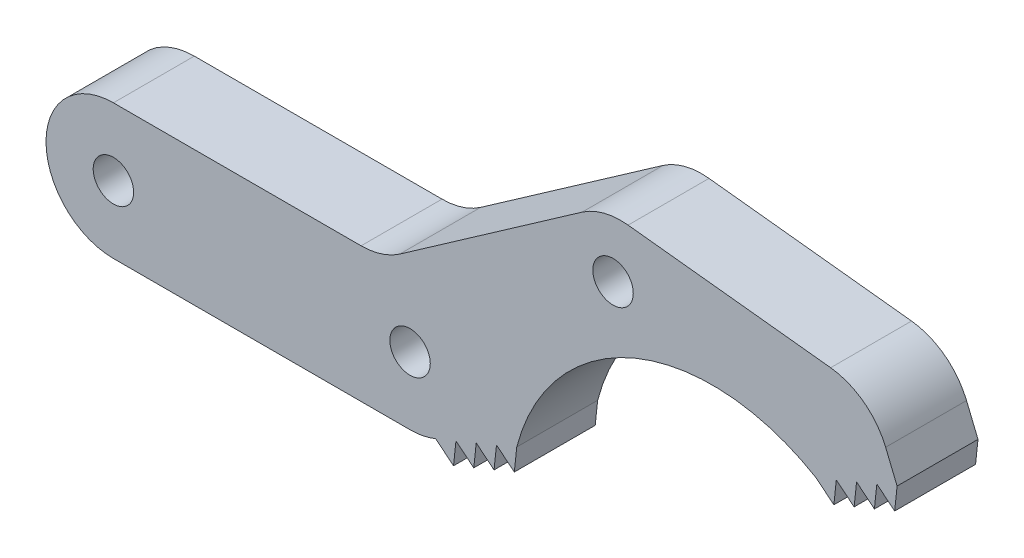
SolidWorks part; units mm, degrees
material "PET"
ref_plane "Front Plane" through (0, 0, 0) normal (0, 0, 1) x (1, 0, 0)
ref_plane "Top Plane" through (0, 0, 0) normal (0, 1, 0) x (1, 0, 0)
ref_plane "Right Plane" through (0, 0, 0) normal (1, 0, 0) x (0, 0, -1)
sketch "Sketch1" plane through (0, 0, 0) normal (0, 0, 1) x (1, 0, 0)
  line L0 (0, 0) -> (22, 0) construction
  line L1 (0, 5) -> (22, 5)
  line L2 (0, -5) -> (22, -5)
  line L3 (19.9443, 5) -> (23.9013, -4.6244) construction
  line L4 (23.9013, -4.6244) -> (58.1218, 9.4454) construction
  line L5 (58.1218, 9.4454) -> (54.1647, 19.0697) construction
  line L6 (54.1647, 19.0697) -> (19.9443, 5) construction
  line L7 (22, 0) -> (56.1433, 14.2576) construction
  line L8 (41.0116, 2.4105) -> (37.0545, 12.0349) construction
  line L9 (52.1101, 6.9736) -> (58.1218, 9.4454) construction
  line L10 (29.913, -2.1527) -> (23.9013, -4.6244) construction
  line L11 (58.1218, 9.4454) -> (56.1433, 14.2576)
  line L12 (19.9443, 5) -> (36.3026, 16.437)
  line L13 (36.3026, 16.437) -> (56.1433, 14.2576)
  line L14 (25.2232, -5.7027) -> (29.732, -3.849) construction
  line L15 (23.9013, -4.6244) -> (25.2232, -5.7027)
  line L16 (25.2232, -5.7027) -> (25.4042, -4.0065)
  line L17 (25.4042, -4.0065) -> (26.7261, -5.0848)
  line L18 (26.7261, -5.0848) -> (26.9072, -3.3885)
  line L19 (26.9072, -3.3885) -> (28.229, -4.4669)
  line L20 (28.229, -4.4669) -> (28.4101, -2.7706)
  line L21 (28.4101, -2.7706) -> (29.732, -3.849)
  line L28 (29.732, -3.849) -> (29.913, -2.1527)
  line L29 (53.432, 5.8953) -> (57.9407, 7.7491) construction
  line L30 (52.1101, 6.9736) -> (53.432, 5.8953)
  line L31 (53.432, 5.8953) -> (53.613, 7.5916)
  line L32 (53.613, 7.5916) -> (54.9349, 6.5132)
  line L33 (54.9349, 6.5132) -> (55.116, 8.2095)
  line L34 (55.116, 8.2095) -> (56.4378, 7.1311)
  line L35 (56.4378, 7.1311) -> (56.6189, 8.8274)
  line L36 (56.6189, 8.8274) -> (57.9407, 7.7491)
  line L37 (57.9407, 7.7491) -> (58.1218, 9.4454)
  line L38 (22, 0) -> (37.424, 10.7837) construction
  arc A0 (0, 5) -> (0, -5) centre (0, 0) ccw
  arc A1 (22, -5) -> (22, 5) centre (22, 0) ccw
  arc A3 (29.913, -2.1527) -> (52.1101, 6.9736) centre (44.4339, -5.9134) cw
  circle A4 centre (0, 0) radius 1.5
  circle A5 centre (22, 0) radius 1.5
  circle A7 centre (37.0545, 12.0349) radius 1.5
  point P3 (11, 0)
  point P21 (38.73, 7.9598)
  dimension "D6" = 6.5
  dimension "D9" = 1.5
  dimension "D8" = 1.5
  dimension "D4" = 157.65
  dimension "D1" = 10
  dimension "D2" = 22
  dimension "D3" = 2.0557
  dimension "D5" = 10.4061
  dimension "D7" = 5.2031
  dimension "34" = 37
extrude "Boss-Extrude1" add sketch "Sketch1" along normal blind 6
fillet "Fillet2" radius 5 3 edges at (56.1433, 14.2576, 3) (36.3026, 16.437, 3) (19.9443, 5, 3)
